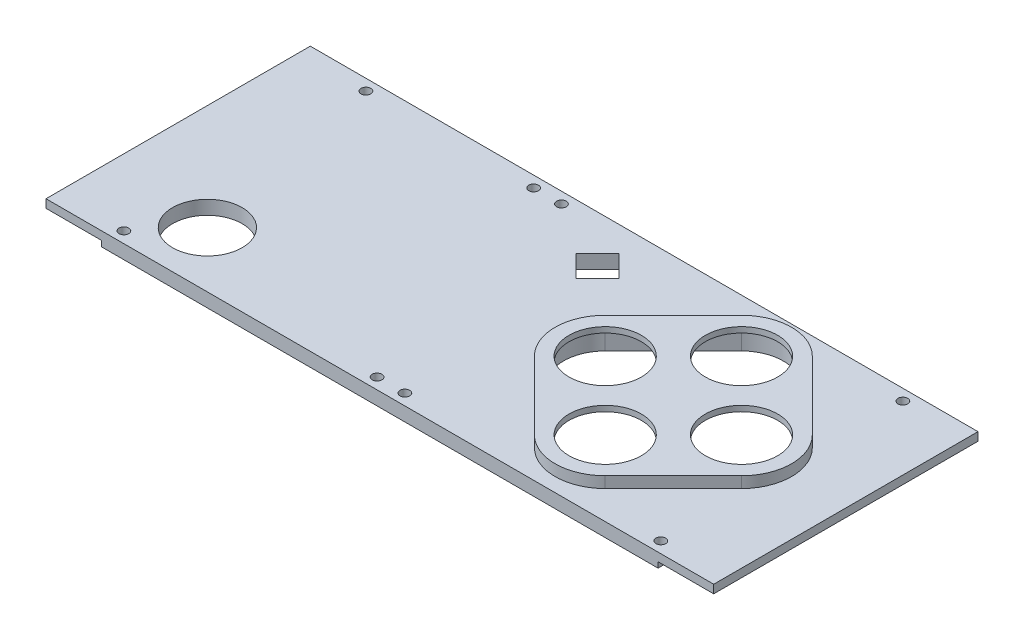
SolidWorks part; units mm, degrees
ref_plane "Front Plane" through (0, 0, 0) normal (0, 0, 1) x (1, 0, 0)
ref_plane "Top Plane" through (0, 0, 0) normal (0, 1, 0) x (1, 0, 0)
ref_plane "Right Plane" through (0, 0, 0) normal (1, 0, 0) x (0, 0, -1)
sketch "Sketch1" plane through (0, 0, 0) normal (0, 1, 0) x (1, 0, 0)
  line L1 (-100, 47.5) -> (100, 47.5)
  line L2 (-100, 47.5) -> (-100, -47.5)
  line L3 (-100, -47.5) -> (100, -47.5)
  line L4 (100, 47.5) -> (100, -47.5)
  line L5 (-100, 47.5) -> (100, -47.5) construction
  line L6 (-100, -47.5) -> (100, 47.5) construction
  circle A0 centre (-96, 43.5) radius 1.75
  circle A1 centre (-96, -43.5) radius 1.75
  circle A2 centre (97, 43.5) radius 1.75
  circle A3 centre (97, -43.5) radius 1.75
  point P0 (0, 0)
  point P14 (0, 0)
  dimension "D4" = 3.5
  dimension "D1" = 200
  dimension "D2" = 95
  dimension "D3" = 4
  dimension "D5" = 4
  dimension "D6" = 4
  dimension "D7" = 4
  dimension "D8" = 3
  dimension "D9" = 4
  dimension "D10" = 4
  dimension "D11" = 3
extrude "Boss-Extrude1" add sketch "Sketch1" along normal blind 5
sketch "Sketch2" plane through (0, 5, 0) normal (0, 1, 0) x (1, 0, 0)
  line L0 (-100, 47.5) -> (-100, -47.5) construction
  line L1 (-100, -47.5) -> (100, -47.5) construction
  line L2 (100, 0) -> (58, 0) construction
  line L3 (100, -47.5) -> (100, 47.5) construction
  line L4 (58, 24.5) -> (58, -24.5) construction
  line L5 (33.5, 0) -> (82.5, 0) construction
  line L6 (22.8934, -10.6066) -> (47.3934, -35.1066)
  line L7 (68.6066, -35.1066) -> (93.1066, -10.6066)
  line L8 (47.3934, 35.1066) -> (22.8934, 10.6066)
  line L9 (68.6066, 35.1066) -> (93.1066, 10.6066)
  circle A0 centre (-82, -27.5) radius 12.5
  circle A1 centre (58, 24.5) radius 15
  circle A2 centre (58, -24.5) radius 15
  circle A3 centre (82.5, 0) radius 15
  circle A4 centre (33.5, 0) radius 15
  point P13 (58, 0)
  point P17 (58, 0)
  point P29 (43, 27.4728)
  point P30 (0, 0)
  dimension "D3" = 25
  dimension "D4" = 30
  dimension "D1" = 18
  dimension "D2" = 20
  dimension "D5" = 42
  dimension "D6" = 23
extrude "Cut-Extrude1" cut sketch "Sketch2" against normal up to surface (5 mm away) contours A4 | A4 L6 A2 L7 A3 L9 A1 L8 | A2 | A3 | A1 | A0 up to face at (0, 0, 0)
sketch "Sketch4" plane through (0, 0, 0) normal (0, -1, 0) x (1, 0, 0)
  line L0 (-100, -47.5) -> (-100, 47.5) construction
  line L1 (-93.5, 41) -> (-71.5, 41)
  line L2 (-93.5, 41) -> (-93.5, -41)
  line L3 (-93.5, -41) -> (-71.5, -41)
  line L4 (-71.5, 41) -> (-71.5, -41)
  line L5 (-93.5, 41) -> (-71.5, -41) construction
  line L6 (-93.5, -41) -> (-71.5, 41) construction
  line L7 (-100, 0) -> (-82.5, 0) construction
  line L8 (-82.5, 0) -> (-82.5, -19.5) construction
  line L9 (-90.5, -1) -> (-74.5, -1)
  line L10 (-90.5, -1) -> (-90.5, -38)
  line L11 (-90.5, -38) -> (-74.5, -38)
  line L12 (-74.5, -1) -> (-74.5, -38)
  line L13 (-90.5, -1) -> (-74.5, -38) construction
  line L14 (-90.5, -38) -> (-74.5, -1) construction
  point P0 (-82.5, 0)
  point P11 (-82.5, -19.5)
  circle M17 centre (-82, 27.5) radius 12.5
  dimension "D1" = 22
  dimension "D2" = 6.5
  dimension "D3" = 82
  dimension "D4" = 3
  dimension "D5" = 3
  dimension "D6" = 40
extrude "Boss-Extrude2" add sketch "Sketch4" along normal blind 4.2 contours L4 L2 L3 L9 L12 L11 L10 M17
sketch "Sketch5" plane through (0, 5, 0) normal (0, 1, 0) x (1, 0, 0)
  circle A0 centre (-82, -27.5) radius 17
  dimension "D1" = 34
sketch "Sketch6" plane through (0, 5, 0) normal (0, 1, 0) x (1, 0, 0)
  line L0 (-100, -47.5) -> (100, -47.5) construction
  line L1 (-100, 47.5) -> (-120, 47.5)
  line L2 (-100, 47.5) -> (-100, -47.5)
  line L3 (-100, -47.5) -> (-120, -47.5)
  line L4 (-120, 47.5) -> (-120, -47.5)
  line L5 (100, 47.5) -> (120, 47.5)
  line L6 (100, 47.5) -> (100, -47.5)
  line L7 (100, -47.5) -> (120, -47.5)
  line L8 (120, 47.5) -> (120, -47.5)
  dimension "D1" = 20
extrude "Boss-Extrude3" add sketch "Sketch6" against normal blind 3
sketch "Sketch8" plane through (0, 5, 0) normal (0, 1, 0) x (1, 0, 0)
  line L20 (70.7279, -37.2279) -> (95.2279, -12.7279)
  line L21 (20.7721, -12.7279) -> (45.2721, -37.2279)
  line L22 (45.2721, 37.2279) -> (20.7721, 12.7279)
  line L23 (95.2279, 12.7279) -> (70.7279, 37.2279)
  line L24 (70.7279, -37.2279) -> (95.2279, -12.7279)
  line L25 (20.7721, -12.7279) -> (45.2721, -37.2279)
  line L26 (45.2721, 37.2279) -> (20.7721, 12.7279)
  line L27 (95.2279, 12.7279) -> (70.7279, 37.2279)
  line L48 (22.8934, -10.6066) -> (47.3934, -35.1066)
  line L49 (68.6066, -35.1066) -> (93.1066, -10.6066)
  line L50 (93.1066, 10.6066) -> (68.6066, 35.1066)
  line L51 (47.3934, 35.1066) -> (22.8934, 10.6066)
  line L52 (22.8934, -10.6066) -> (47.3934, -35.1066)
  line L53 (68.6066, -35.1066) -> (93.1066, -10.6066)
  line L54 (93.1066, 10.6066) -> (68.6066, 35.1066)
  line L55 (47.3934, 35.1066) -> (22.8934, 10.6066)
  arc A8 (95.2279, -12.7279) -> (95.2279, 12.7279) centre (82.5, 0) ccw
  arc A9 (45.2721, -37.2279) -> (70.7279, -37.2279) centre (58, -24.5) ccw
  arc A10 (20.7721, 12.7279) -> (20.7721, -12.7279) centre (33.5, 0) ccw
  arc A11 (70.7279, 37.2279) -> (45.2721, 37.2279) centre (58, 24.5) ccw
  arc A12 (95.2279, -12.7279) -> (95.2279, 12.7279) centre (82.5, 0) ccw
  arc A13 (45.2721, -37.2279) -> (70.7279, -37.2279) centre (58, -24.5) ccw
  arc A14 (20.7721, 12.7279) -> (20.7721, -12.7279) centre (33.5, 0) ccw
  arc A15 (70.7279, 37.2279) -> (45.2721, 37.2279) centre (58, 24.5) ccw
  arc A32 (22.8934, 10.6066) -> (22.8934, -10.6066) centre (33.5, 0) ccw
  arc A33 (47.3934, -35.1066) -> (68.6066, -35.1066) centre (58, -24.5) ccw
  arc A34 (93.1066, -10.6066) -> (93.1066, 10.6066) centre (82.5, 0) ccw
  arc A35 (68.6066, 35.1066) -> (47.3934, 35.1066) centre (58, 24.5) ccw
  arc A36 (22.8934, 10.6066) -> (22.8934, -10.6066) centre (33.5, 0) ccw
  arc A37 (47.3934, -35.1066) -> (68.6066, -35.1066) centre (58, -24.5) ccw
  arc A38 (93.1066, -10.6066) -> (93.1066, 10.6066) centre (82.5, 0) ccw
  arc A39 (68.6066, 35.1066) -> (47.3934, 35.1066) centre (58, 24.5) ccw
  dimension "D1" = 3
  dimension "D2" = 0
extrude "Boss-Extrude4" add sketch "Sketch8" along normal blind 4
sketch "Sketch9" plane through (0, 9, 0) normal (0, 1, 0) x (1, 0, 0)
  line L24 (22.8934, -10.6066) -> (47.3934, -35.1066)
  line L25 (68.6066, -35.1066) -> (93.1066, -10.6066)
  line L26 (93.1066, 10.6066) -> (68.6066, 35.1066)
  line L27 (47.3934, 35.1066) -> (22.8934, 10.6066)
  line L28 (22.8934, -10.6066) -> (47.3934, -35.1066)
  line L29 (68.6066, -35.1066) -> (93.1066, -10.6066)
  line L30 (93.1066, 10.6066) -> (68.6066, 35.1066)
  line L31 (47.3934, 35.1066) -> (22.8934, 10.6066)
  circle A0 centre (58, 24.5) radius 13
  circle A1 centre (82.5, 0) radius 13
  circle A2 centre (58, -24.5) radius 13
  circle A3 centre (33.5, 0) radius 13
  arc A24 (22.8934, 10.6066) -> (22.8934, -10.6066) centre (33.5, 0) ccw
  arc A25 (47.3934, -35.1066) -> (68.6066, -35.1066) centre (58, -24.5) ccw
  arc A26 (93.1066, -10.6066) -> (93.1066, 10.6066) centre (82.5, 0) ccw
  arc A27 (68.6066, 35.1066) -> (47.3934, 35.1066) centre (58, 24.5) ccw
  arc A28 (22.8934, 10.6066) -> (22.8934, -10.6066) centre (33.5, 0) ccw
  arc A29 (47.3934, -35.1066) -> (68.6066, -35.1066) centre (58, -24.5) ccw
  arc A30 (93.1066, -10.6066) -> (93.1066, 10.6066) centre (82.5, 0) ccw
  arc A31 (68.6066, 35.1066) -> (47.3934, 35.1066) centre (58, 24.5) ccw
  dimension "D1" = 26
  dimension "D2" = 0
extrude "Boss-Extrude5" add sketch "Sketch9" against normal blind 2
sketch "Sketch10" plane through (0, 5, 0) normal (0, 1, 0) x (1, 0, 0)
  line L0 (0, 47.5) -> (0, 38.5) construction
  line L1 (120, 47.5) -> (-120, 47.5) construction
  line L2 (0, 38.5) -> (-7.7782, 30.7218)
  line L3 (-7.7782, 30.7218) -> (0, 22.9437)
  line L4 (0, 22.9437) -> (7.7782, 30.7218)
  line L5 (0, 38.5) -> (7.7782, 30.7218)
  line L6 (0, 38.5) -> (0, 22.9437) construction
  dimension "D1" = 9
  dimension "D2" = 11
extrude "Cut-Extrude2" cut sketch "Sketch10" against normal up to surface (5 mm away) up to face at (97, 0, 45.25)
sketch "Sketch11" plane through (0, 5, 0) normal (0, 1, 0) x (1, 0, 0)
  line L0 (-7.7782, 30.7218) -> (-30.7218, 30.7218) construction
  line L1 (0, 22.9437) -> (0, 0) construction
  line L2 (-30.7218, 30.7218) -> (0, 0)
  line L3 (0, 0) -> (0, -47.5)
  line L4 (-120, -47.5) -> (120, -47.5) construction
  line L5 (-30.7218, 30.7218) -> (-30.7218, 47.5)
  line L6 (120, 47.5) -> (-120, 47.5) construction
  line L7 (-120, 0) -> (0, 0) construction
  line L8 (-120, 47.5) -> (-120, -47.5) construction
  line L9 (-35.7218, 43.5) -> (-25.7218, 43.5) construction
  line L10 (-120, 47.5) -> (120, 47.5)
  line L11 (-120, 47.5) -> (-120, -47.5)
  line L12 (-120, -47.5) -> (120, -47.5)
  line L13 (120, 47.5) -> (120, -47.5)
  line L14 (-5, -43.5) -> (5, -43.5) construction
  circle A0 centre (-5, -43.5) radius 1.75
  circle A1 centre (5, -43.5) radius 1.75
  circle A2 centre (-25.7218, 43.5) radius 1.75
  circle A3 centre (-35.7218, 43.5) radius 1.75
  point P31 (0, 0)
  point P34 (-30.7218, 43.5)
  point P37 (0, -43.5)
  point P38 (0, 0)
  point P39 (0, 0)
  point P40 (0, 0)
  dimension "D2" = 3.5
  dimension "D1" = 10
  dimension "D3" = 4
  dimension "D4" = 4
extrude "Cut-Extrude3" cut sketch "Sketch11" along direction (0, 1, 0) on the side against the normal blind 10 contours A3 | A2 | A1 | A0
sketch "Sketch14" plane through (0, 5, 0) normal (0, 1, 0) x (1, 0, 0)
  line L0 (-7.7782, 30.7218) -> (-30.7218, 30.7218) construction
  line L1 (0, 22.9437) -> (0, 0) construction
  line L2 (-30.7218, 30.7218) -> (0, 0)
  line L3 (0, 0) -> (0, -47.5)
  line L4 (-120, -47.5) -> (120, -47.5) construction
  line L5 (-30.7218, 30.7218) -> (-30.7218, 47.5)
  line L6 (120, 47.5) -> (-120, 47.5) construction
  line L7 (-120, 0) -> (0, 0) construction
  line L8 (-120, 47.5) -> (-120, -47.5) construction
  line L10 (-120, 47.5) -> (120, 47.5)
  line L11 (-120, 47.5) -> (-120, -47.5)
  line L12 (-120, -47.5) -> (120, -47.5)
  line L13 (120, 47.5) -> (120, -47.5)
equation "\"D1@Boss-Extrude4\"=13-5-4"
